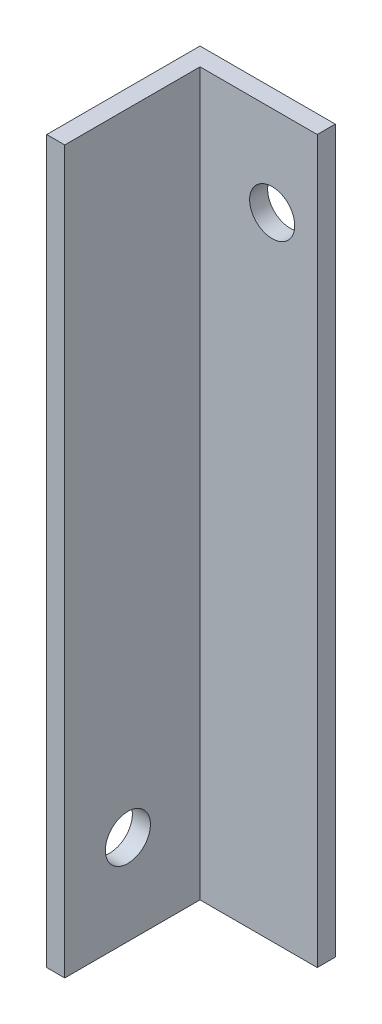
SolidWorks part; units mm, degrees
ref_plane "Plan de face" through (0, 0, 0) normal (0, 0, 1) x (1, 0, 0)
ref_plane "Plan de dessus" through (0, 0, 0) normal (0, 1, 0) x (1, 0, 0)
ref_plane "Plan de droite" through (0, 0, 0) normal (1, 0, 0) x (0, 0, -1)
sketch "Esquisse1" plane through (0, 0, 0) normal (0, 0, 1) x (1, 0, 0)
  line L1 (0, 0) -> (15, 0)
  line L2 (0, 0) -> (0, -80)
  line L3 (0, -80) -> (15, -80)
  line L4 (15, 0) -> (15, -80)
  dimension "D1" = 15
  dimension "D2" = 80
extrude "Boss.-Extru.1" add sketch "Esquisse1" along normal blind 2
sketch "Esquisse2" plane through (0, 0, 2) normal (0, 0, 1) x (1, 0, 0)
  line L0 (0, -80) -> (15, -80) construction
  line L1 (0, 0) -> (2, 0)
  line L2 (0, 0) -> (0, -80)
  line L3 (0, -80) -> (2, -80)
  line L4 (2, 0) -> (2, -80)
  dimension "D1" = 2
extrude "Boss.-Extru.2" add sketch "Esquisse2" along normal blind 15
sketch "Esquisse3" plane through (0, 0, 2) normal (0, 0, 1) x (1, 0, 0)
  line L2 (15, -80) -> (15, 0) construction
  line L3 (15, 0) -> (2, 0) construction
  circle A0 centre (10, -10) radius 2.5
  dimension "D1" = 5
  dimension "D2" = 10
extrude "Enlèv. mat.-Extru.1" cut sketch "Esquisse3" against normal blind 20
sketch "Esquisse4" plane through (0, 0, 0) normal (-1, 0, 0) x (0, 0, 1)
  line L0 (0, 0) -> (0, -80) construction
  line L1 (17, -80) -> (0, -80) construction
  circle A0 centre (10, -70) radius 2.5
  dimension "D1" = 5
  dimension "D2" = 10
  dimension "D3" = 10
extrude "Enlèv. mat.-Extru.2" cut sketch "Esquisse4" against normal blind 20
